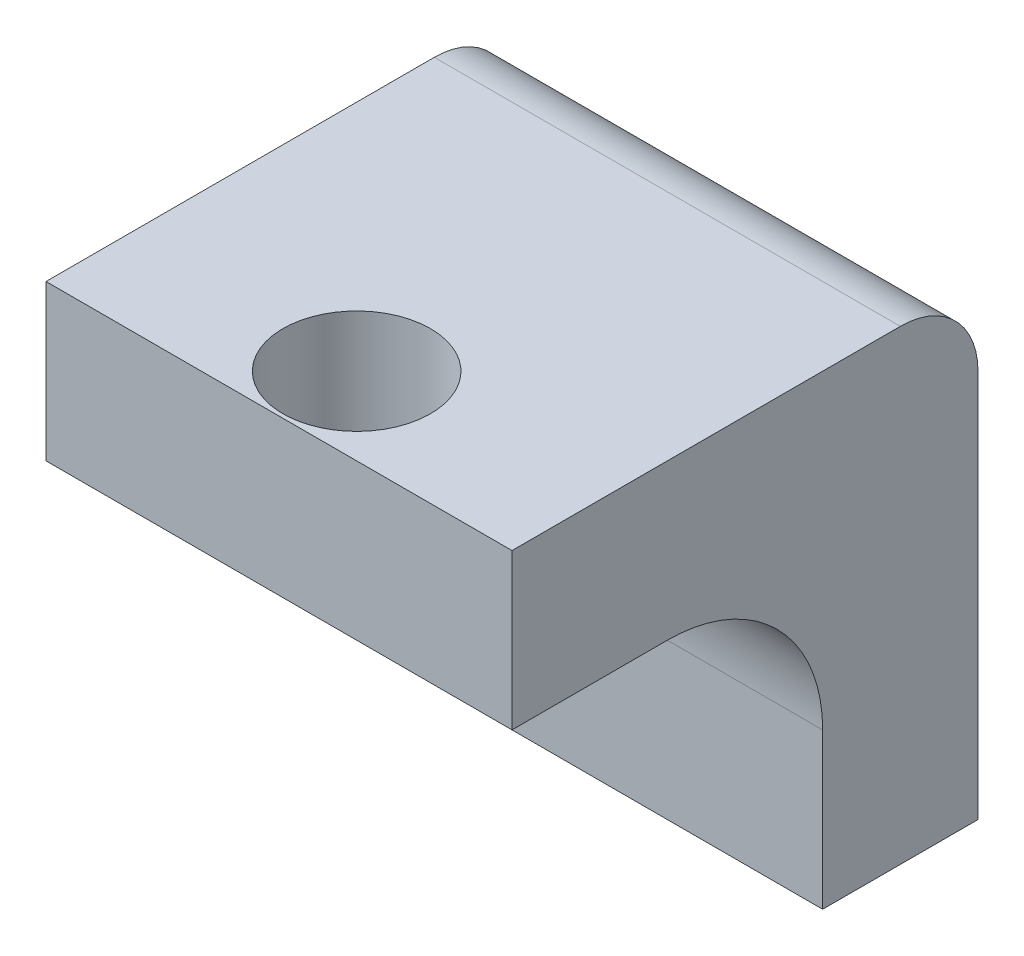
SolidWorks part; units mm, degrees
ref_plane "Front Plane" through (0, 0, 0) normal (0, 0, 1) x (1, 0, 0)
ref_plane "Top Plane" through (0, 0, 0) normal (0, 1, 0) x (1, 0, 0)
ref_plane "Right Plane" through (0, 0, 0) normal (1, 0, 0) x (0, 0, -1)
sketch "Sketch1" plane through (0, 0, 0) normal (0, 0, 1) x (1, 0, 0)
  line L1 (0, 0) -> (30, 0)
  line L2 (0, 0) -> (0, 30)
  line L3 (0, 30) -> (30, 30)
  line L4 (30, 0) -> (30, 30)
  dimension "D1" = 30
  dimension "D2" = 30
extrude "Boss-Extrude3" add sketch "Sketch1" along normal blind 10
sketch "Sketch2" plane through (0, 0, 0) normal (-1, 0, 0) x (0, 0, 1)
  line L0 (10, 30) -> (30, 30)
  line L1 (30, 30) -> (30, 20)
  line L2 (30, 20) -> (10, 20)
  line L3 (10, 30) -> (10, 0) construction
  line L4 (10, 20) -> (10, 30)
extrude "Boss-Extrude5" add sketch "Sketch2" against normal blind 30 contours L4 L0 L1 L2
fillet "Fillet1" radius 10 1 edges at (15, 20, 10)
ref_plane "Plane1" through (0, 20, 20) normal (1, 0, 0) x (0, 0, -1)
ref_plane "Plane2" through (0, 20, 20) normal (1, 0, 0) x (0, 0, -1)
sketch "Sketch8" plane through (0, 20, 0) normal (0, -1, 0) x (1, 0, 0)
  line L0 (0, 20) -> (30, 20) construction
  line L1 (0, 11.75) -> (0, 28.25) construction
  circle A0 centre (15, 25) radius 4.75
  dimension "D1" = 9.5
  dimension "D2" = 5
  dimension "D3" = 15
extrude "Cut-Extrude6" cut sketch "Sketch8" against normal through all contours A0
fillet "Fillet3" radius 5 1 edges at (15, 30, 0)
